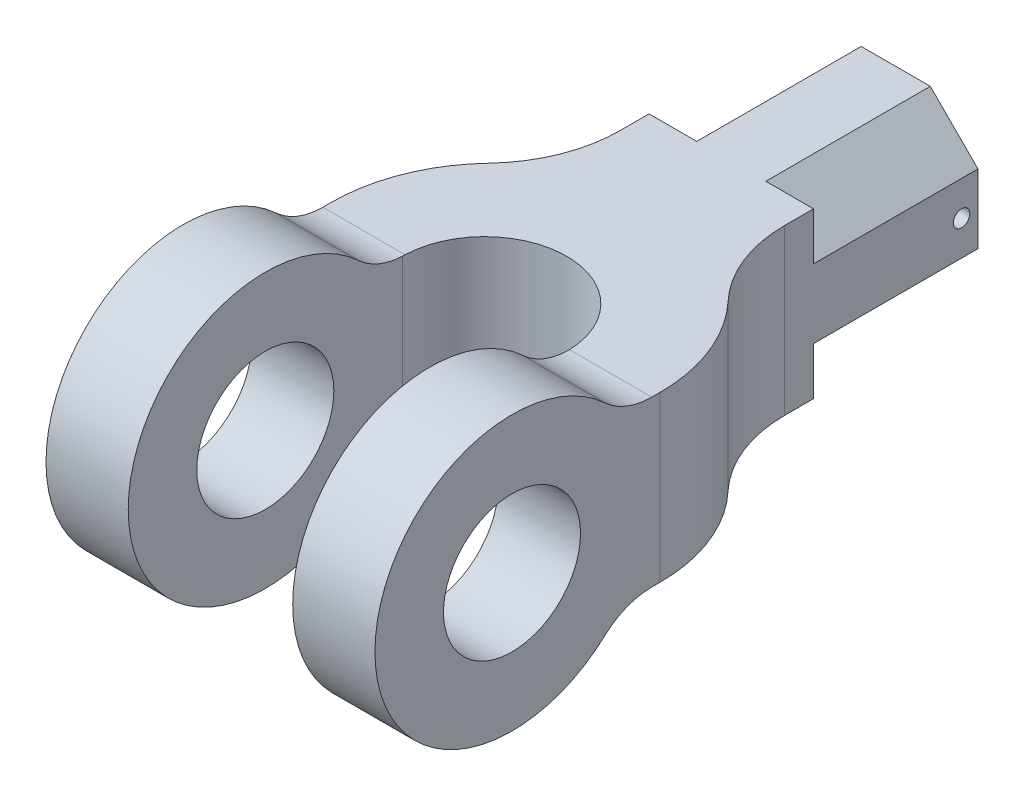
SolidWorks part; units mm, degrees
ref_plane "Front Plane" through (0, 0, 0) normal (0, 0, 1) x (1, 0, 0)
ref_plane "Top Plane" through (0, 0, 0) normal (0, 1, 0) x (1, 0, 0)
ref_plane "Right Plane" through (0, 0, 0) normal (1, 0, 0) x (0, 0, -1)
sketch "Sketch1" plane through (0, 0, 0) normal (0, 1, 0) x (1, 0, 0)
  line L1 (0, 0) -> (-1200, 0)
  line L2 (0, 0) -> (0, 2500)
  line L3 (0, 2500) -> (-1200, 2500)
  line L4 (-1200, 0) -> (-1200, 2500)
  dimension "D1" = 2500
  dimension "D2" = 1200
extrude "Boss-Extrude1" add sketch "Sketch1" along normal blind 1000
sketch "Sketch2" plane through (0, 1000, 0) normal (0, 1, 0) x (1, 0, 0)
  line L0 (-600, 2500) -> (-600, 0) construction
  line L1 (0, 2500) -> (-1200, 2500) construction
  line L2 (-1200, 0) -> (0, 0) construction
  line L3 (-900, 2500) -> (-900, 1794.9834)
  line L4 (-300, 2500) -> (-300, 1794.9834)
  line L5 (-900, 1000) -> (-900, 0)
  line L6 (-300, 1000) -> (-300, 0)
  circle A0 centre (-600, 1000) radius 300
  arc A1 (-1036.3636, 1451.8092) -> (-163.6364, 1451.8092) centre (-600, 1040) ccw
  arc A2 (-163.6364, 1451.8092) -> (-300, 1794.9834) centre (200, 1794.9834) cw
  arc A3 (-900, 1794.9834) -> (-1036.3636, 1451.8092) centre (-1400, 1794.9834) cw
  point P15 (-300, 1559.6152)
  point P18 (-900, 1559.6152)
  line M6 (0, 0) -> (0, 2500)
  line M7 (0, 2500) -> (-1200, 2500)
  line M8 (-1200, 2500) -> (-1200, 0)
  line M9 (-1200, 0) -> (0, 0)
  dimension "D1" = 600
  dimension "D2" = 1200
  dimension "D6" = 500
  dimension "D3" = 1500
  dimension "D4" = 40
  dimension "D5" = 300
extrude "Cut-Extrude1" cut sketch "Sketch2" against normal blind 1000 contours A3 L3 A1 M7 M8 | A2 A1 L4 M6 M7 | L0 A1 L5 M9 | L0 A0 L5 A1 | L0 A0 | A0 L0 | A0 L0 A1 L6 | A1 L0 L6 M9
sketch "Sketch3" plane through (0, 0, 0) normal (1, 0, 0) x (0, 0, -1)
  line L0 (0, 1000) -> (1040, 1000) construction
  line L1 (0, 1000) -> (0, 0) construction
  line L2 (0, 0) -> (1040, 0) construction
  line L3 (500, 500) -> (2500, 500) construction
  line L4 (2500, 0) -> (2500, 1000) construction
  line L5 (0, 1000) -> (0, 0)
  line L6 (2500, 800) -> (1009.902, 800)
  line L7 (2500, 800) -> (2500, 200)
  line L8 (2500, 200) -> (1009.902, 200)
  line L16 (1451.8092, 1000) -> (1040, 1000) construction
  line L17 (1794.9834, 1000) -> (1451.8092, 1000) construction
  line L18 (2500, 1000) -> (1794.9834, 1000) construction
  line L19 (2500, 0) -> (1794.9834, 0) construction
  line L20 (1451.8092, 0) -> (1794.9834, 0) construction
  line L21 (1040, 0) -> (1451.8092, 0) construction
  line L22 (0, 0) -> (1040, 0)
  line L23 (1040, 0) -> (1451.8092, 0)
  line L24 (1451.8092, 0) -> (1794.9834, 0)
  line L25 (2500, 0) -> (1794.9834, 0)
  line L26 (2500, 0) -> (2500, 1000)
  line L27 (2500, 1000) -> (1794.9834, 1000)
  line L28 (1794.9834, 1000) -> (1451.8092, 1000)
  line L29 (1451.8092, 1000) -> (1040, 1000)
  line L30 (0, 1000) -> (1040, 1000)
  arc A0 (839.9346, 866.6667) -> (839.9346, 133.3333) centre (500, 500) ccw
  circle A1 centre (500, 500) radius 250
  arc A2 (839.9346, 133.3333) -> (1009.902, 200) centre (1009.902, -50) cw
  arc A3 (839.9346, 866.6667) -> (1009.902, 800) centre (1009.902, 1050) ccw
  line M8 (0, 0) -> (1040, 0)
  line M9 (1040, 0) -> (1040, 1000)
  line M10 (1040, 1000) -> (0, 1000)
  line M11 (0, 1000) -> (0, 0)
  dimension "D1" = 500
  dimension "D2" = 250
  dimension "D3" = 600
extrude "Cut-Extrude4" cut sketch "Sketch3" against normal through all contours A0 L30 M11 | A0 A3 L6 M9 M10 | L28 L29 L6 L26 L27 M9 | L25 L26 L8 L23 L24 M9 | A2 A0 L22 L8 M9 | A0 L5 M8
sketch "Sketch5" plane through (0, 0, -2500) normal (0, 0, -1) x (-1, 0, 0)
  line L0 (300, 200) -> (900, 800) construction
  line L1 (900, 800) -> (900, 626)
  line L2 (900, 200) -> (900, 800) construction
  line L3 (900, 626) -> (726, 800)
  line L4 (900, 800) -> (300, 800) construction
  line L5 (726, 800) -> (900, 800)
  line L6 (900, 374) -> (900, 200)
  line L7 (900, 200) -> (726, 200)
  line L8 (726, 200) -> (900, 374)
  line L9 (474, 200) -> (300, 200)
  line L10 (300, 200) -> (300, 374)
  line L11 (300, 374) -> (474, 200)
  line L12 (300, 626) -> (300, 800)
  line L13 (300, 800) -> (474, 800)
  line L14 (474, 800) -> (300, 626)
  circle A0 centre (600, 500) radius 250
  point P24 (600, 500)
  line M5 (900, 800) -> (300, 800)
  line M6 (300, 800) -> (300, 200)
  line M7 (300, 200) -> (900, 200)
  line M8 (900, 200) -> (900, 800)
  dimension "D1" = 500
  dimension "D2" = 174
  dimension "D3" = 174
  dimension "D4" = 4
extrude "Cut-Extrude6" cut sketch "Sketch5" against normal blind 600 contours L14 M5 M6 | L0 L3 M8 | L8 M7 M8 | L0 L11 M7 | L0 L11 M6 | L3 L0 M5
sketch "Sketch6" plane through (0, 0, -2500) normal (0, 0, -1) x (-1, 0, 0)
  line L0 (900, 800) -> (300, 200) construction
  circle A0 centre (600, 500) radius 250
  dimension "D1" = 500
extrude "Cut-Extrude7" cut sketch "Sketch6" against normal blind 120
sketch "Sketch7" plane through (-900, 0, 0) normal (-1, 0, 0) x (0, 0, 1)
  line L0 (-2500, 374) -> (-2500, 626) construction
  circle A0 centre (-2440, 500) radius 30
  dimension "D1" = 60
  dimension "D2" = 60
extrude "Cut-Extrude9" cut sketch "Sketch7" against normal through all
sketch "Sketch8" plane through (0, 0, 0) normal (1, 0, 0) x (0, 0, -1)
  line L0 (1040, 500) -> (0, 500) construction
  line L1 (1040, 200) -> (1040, 800) construction
  arc A0 (839.9346, 866.6667) -> (839.9346, 133.3333) centre (500, 500) ccw construction
  circle A1 centre (500, 500) radius 250
  dimension "D1" = 500
extrude "Cut-Extrude10" cut sketch "Sketch8" against normal through all
